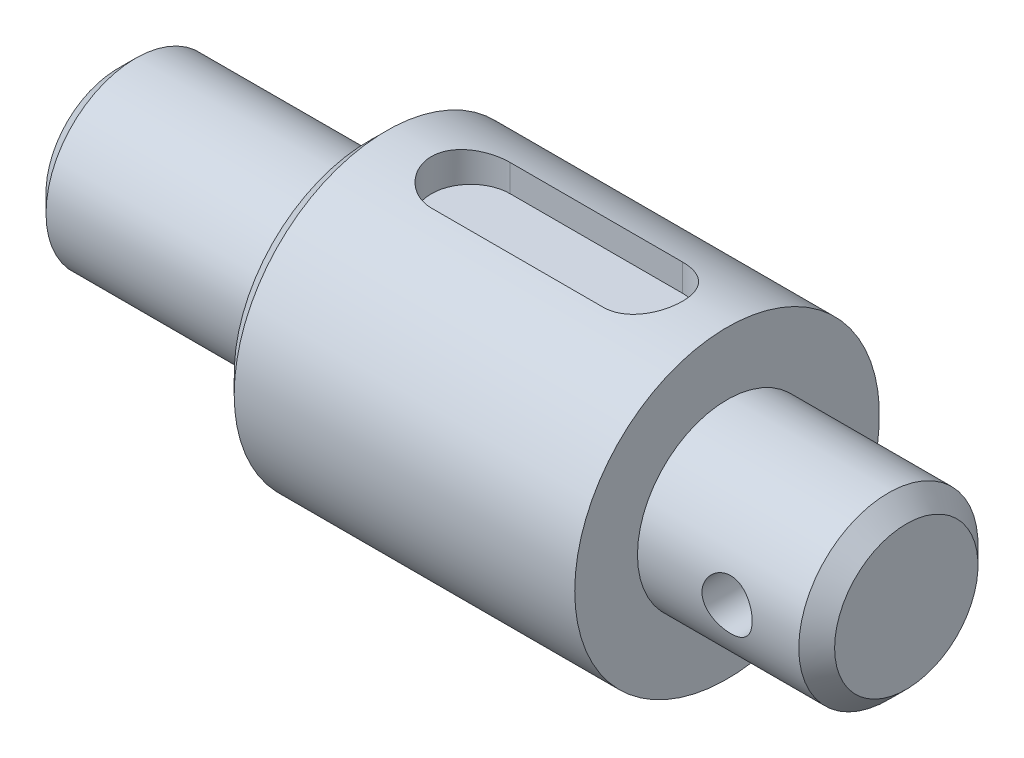
SolidWorks part; units mm, degrees
ref_plane "Спереди" through (0, 0, 0) normal (0, 0, 1) x (1, 0, 0)
ref_plane "Сверху" through (0, 0, 0) normal (0, 1, 0) x (1, 0, 0)
ref_plane "Справа" through (0, 0, 0) normal (1, 0, 0) x (0, 0, -1)
sketch "Эскиз1" plane through (0, 0, 0) normal (0, 0, 1) x (1, 0, 0)
  line L0 (0, 0) -> (40139.6787, 0) construction
  line L1 (-70, 0) -> (-70, 25)
  line L2 (-70, 25) -> (0, 25)
  line L3 (0, 25) -> (0, 42.5)
  line L4 (0, 42.5) -> (100, 42.5)
  line L5 (100, 42.5) -> (100, 25)
  line L6 (100, 25) -> (150, 25)
  line L7 (150, 25) -> (150, 0)
  line L8 (150, 0) -> (-70, 0)
  line L9 (0, 0) -> (0, 73.6858) construction
  dimension "D1" = 50
  dimension "D2" = 50
  dimension "D3" = 85
  dimension "D4" = 70
  dimension "D5" = 100
  dimension "D6" = 50
revolve "Повернуть1" add sketch "Эскиз1" angle 360 about L0
chamfer "Фаска1" distance 5 angle 45 3 edges at (0, 0, 42.5) (150, 0, 25) (-70, 0, 25)
sketch "Эскиз2" plane through (0, 0, 0) normal (0, 0, 1) x (1, 0, 0)
  line L0 (0, 25) -> (0, 24.5)
  line L1 (0, 25) -> (0, -25) construction
  line L2 (-2, 22.5) -> (-5.0858, 22.5)
  line L3 (-5.7929, 22.7929) -> (-8, 25)
  line L4 (0, 25) -> (-65, 25) construction
  line L5 (-8, 25) -> (0, 25)
  line L6 (0, 0) -> (50000, 0) construction
  line L7 (0, 37.5) -> (0, -37.5) construction
  arc A0 (-5.0858, 22.5) -> (-5.7929, 22.7929) centre (-5.0858, 23.5) cw
  arc A1 (0, 24.5) -> (-2, 22.5) centre (-2, 24.5) cw
  point P13 (0, 23.5386)
  point P17 (0, 22.5)
  point P18 (0, 0)
  point P19 (-5.1611, 25)
  point P20 (-1.9416, 23.9416)
  point P21 (0, 25.25)
  point P24 (-3.0429, 25.0429)
  point P25 (0, 0)
  point P26 (0, 22.6134)
  dimension "D4" = 1
  dimension "D5" = 2
  dimension "D1" = 8
  dimension "D2" = 45
  dimension "D3" = 45
revolve "Вырез-Повернуть1" cut sketch "Эскиз2" angle 360 about L6
sketch "Эскиз3" plane through (0, 0, 0) normal (0, 1, 0) x (1, 0, 0)
  line L0 (28.5, 0) -> (76.5, 0) construction
  line L1 (28.5, 11) -> (76.5, 11)
  line L2 (28.5, -11) -> (76.5, -11)
  line L3 (52.5, 0) -> (52.5, -42.5) construction
  line L4 (5, -42.5) -> (100, -42.5) construction
  arc A0 (28.5, 11) -> (28.5, -11) centre (28.5, 0) ccw
  arc A1 (76.5, -11) -> (76.5, 11) centre (76.5, 0) ccw
  point P3 (52.5, 0)
  dimension "D2" = 11
  dimension "D1" = 48
extrude "Вырез-Вытянуть1" cut sketch "Эскиз3" along normal through all from offset 33.5
ref_plane "Плоскость1" through (125, 0, 0) normal (1, 0, 0) x (0, 0, -1)
sketch "Эскиз4" plane through (125, 0, 0) normal (1, 0, 0) x (0, 0, -1)
  line L0 (-10, 0) -> (-14.0415, 7)
  line L1 (-14.0415, 7) -> (-25, 7)
  line L2 (-25, 7) -> (-25, 0)
  line L5 (-10, 0) -> (-25, 0)
  circle A1 centre (0, 0) radius 25 construction
  point P2 (0, 0)
  point P4 (0, 0)
  point P5 (0, 0)
  point P8 (0, 0)
  point P9 (0, 0)
  point P10 (0, 0)
  point P11 (0, 0)
  point P12 (0, 0)
  point P13 (0, 0)
  point P15 (0, 0)
  point P16 (0, 0)
  point P17 (0, 0)
  point P18 (0, 0)
  point P19 (0, 0)
  point P22 (0, 0)
  dimension "D1" = 60
  dimension "D2" = 10
  dimension "D3" = 7
revolve "Вырез-Повернуть3" cut sketch "Эскиз4" angle 360 about L5
